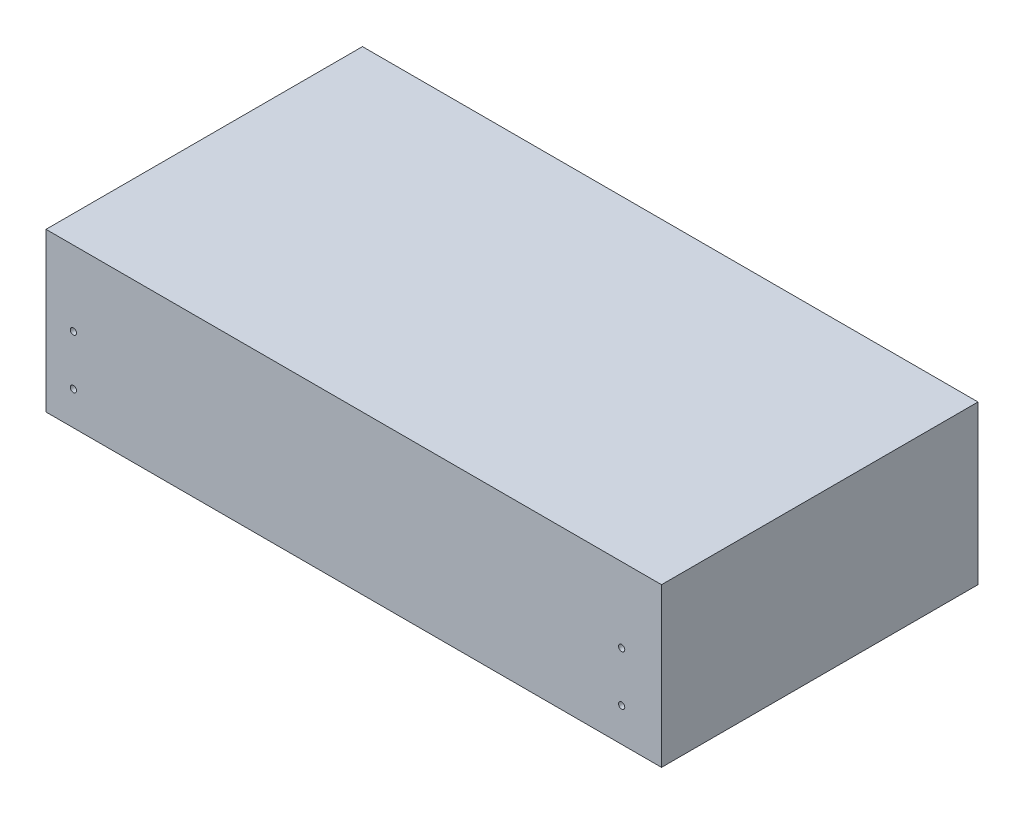
SolidWorks part; units mm, degrees
material "6061-T6 (SS)"
ref_plane "Front Plane" through (0, 0, 0) normal (0, 0, 1) x (1, 0, 0)
ref_plane "Top Plane" through (0, 0, 0) normal (0, 1, 0) x (1, 0, 0)
ref_plane "Right Plane" through (0, 0, 0) normal (1, 0, 0) x (0, 0, -1)
sketch "Sketch1" plane through (0, 0, 0) normal (0, 1, 0) x (1, 0, 0)
  line L0 (-123.5, 63.5) -> (123.5, -63.5) construction
  line L1 (-123.5, -63.5) -> (123.5, -63.5)
  line L2 (-123.5, -63.5) -> (-123.5, 63.5)
  line L3 (-123.5, 63.5) -> (123.5, 63.5)
  line L4 (123.5, -63.5) -> (123.5, 63.5)
  dimension "D1" = 127
  dimension "D2" = 247
extrude "Boss-Extrude1" add sketch "Sketch1" along normal blind 63.5
hole_wizard "M3x0.5 Tapped Hole1" positions "Sketch2" profile "Sketch3" tap size "M3x0.5" standard "ANSI Metric"
sketch "Sketch2" plane through (0, 0, 63.5) normal (0, 0, 1) x (1, 0, 0)
  line L0 (-123.5, 63.5) -> (123.5, 63.5) construction
  line L1 (123.5, 63.5) -> (123.5, 0) construction
  point P0 (-112.5, 33.5)
  point P2 (-112.5, 13.5)
  point P4 (107.5, 13.5)
  point P6 (107.5, 33.5)
  dimension "D1" = 20
  dimension "D2" = 30
  dimension "D3" = 220
  dimension "D4" = 16
sketch "Sketch3" plane through (-112.5, 33.5, 63.5) normal (1, 0, 0) x (0, -1, 0)
  line L0 (0, 0) -> (0, 4.7511)
  line L1 (0, 4.7511) -> (1.25, 4)
  line L2 (1.25, 4) -> (1.25, 0)
  line L5 (1.25, 0) -> (0, 0)
  line L10 (0, 4.7511) -> (-1.25, 4) construction
  line L11 (0, -6.35) -> (0, 107.95) construction
  dimension "Tap Drill Dia." = 2.5
  dimension "Tap Drill Depth" = 4
  dimension "Drill Angle" = 118
cosmetic thread "Hole Thread1" parameters "D1"=4, "D2"=3
cosmetic thread "Hole Thread2" parameters "D1"=4, "D2"=3
cosmetic thread "Hole Thread3" parameters "D1"=4, "D2"=3
cosmetic thread "Hole Thread4" parameters "D1"=4, "D2"=3
mirror "Mirror1" about plane through (0, 0, 0) normal (0, 0, 1) of "M3x0.5 Tapped Hole1"
sketch "Sketch4" plane through (-123.5, 0, 0) normal (-1, 0, 0) x (0, 0, 1)
  line L0 (-63.5, 0) -> (63.5, 0) construction
  line L1 (29.45, 12) -> (48.5, 12)
  line L2 (29.45, 12) -> (29.45, 18.35)
  line L3 (29.45, 18.35) -> (48.5, 18.35)
  line L4 (48.5, 12) -> (48.5, 18.35)
  line L5 (63.5, 63.5) -> (63.5, 0) construction
  dimension "D1" = 19.05
  dimension "D2" = 6.35
  dimension "D3" = 12
  dimension "D4" = 15
extrude "Boss-Extrude2" add sketch "Sketch4" along normal blind 5
sketch "Sketch5" plane through (-128.5, 0, 0) normal (-1, 0, 0) x (0, 0, 1)
  line L0 (29.45, 12) -> (48.5, 12) construction
  line L1 (29.45, 18.35) -> (31.0375, 18.35)
  line L2 (29.45, 18.35) -> (29.45, 12)
  line L3 (29.45, 12) -> (31.0375, 12)
  line L4 (31.0375, 18.35) -> (31.0375, 12)
  line L5 (48.5, 18.35) -> (29.45, 18.35) construction
  line L6 (35.2708, 18.35) -> (36.8583, 18.35)
  line L7 (35.2708, 18.35) -> (35.2708, 12)
  line L8 (35.2708, 12) -> (36.8583, 12)
  line L9 (36.8583, 18.35) -> (36.8583, 12)
  line L10 (31.0375, 15.175) -> (35.2708, 15.175) construction
  line L11 (48.5, 18.35) -> (46.9125, 18.35)
  line L12 (48.5, 18.35) -> (48.5, 12)
  line L13 (48.5, 12) -> (46.9125, 12)
  line L14 (46.9125, 18.35) -> (46.9125, 12)
  line L16 (41.0917, 18.35) -> (42.6792, 18.35)
  line L17 (41.0917, 18.35) -> (41.0917, 12)
  line L18 (41.0917, 12) -> (42.6792, 12)
  line L19 (42.6792, 18.35) -> (42.6792, 12)
  line L20 (36.8583, 17.198) -> (41.0917, 17.198) construction
  line L21 (42.6792, 17.198) -> (46.9125, 17.198) construction
  dimension "D1" = 1.5875
extrude "Boss-Extrude3" add sketch "Sketch5" along normal blind 5
